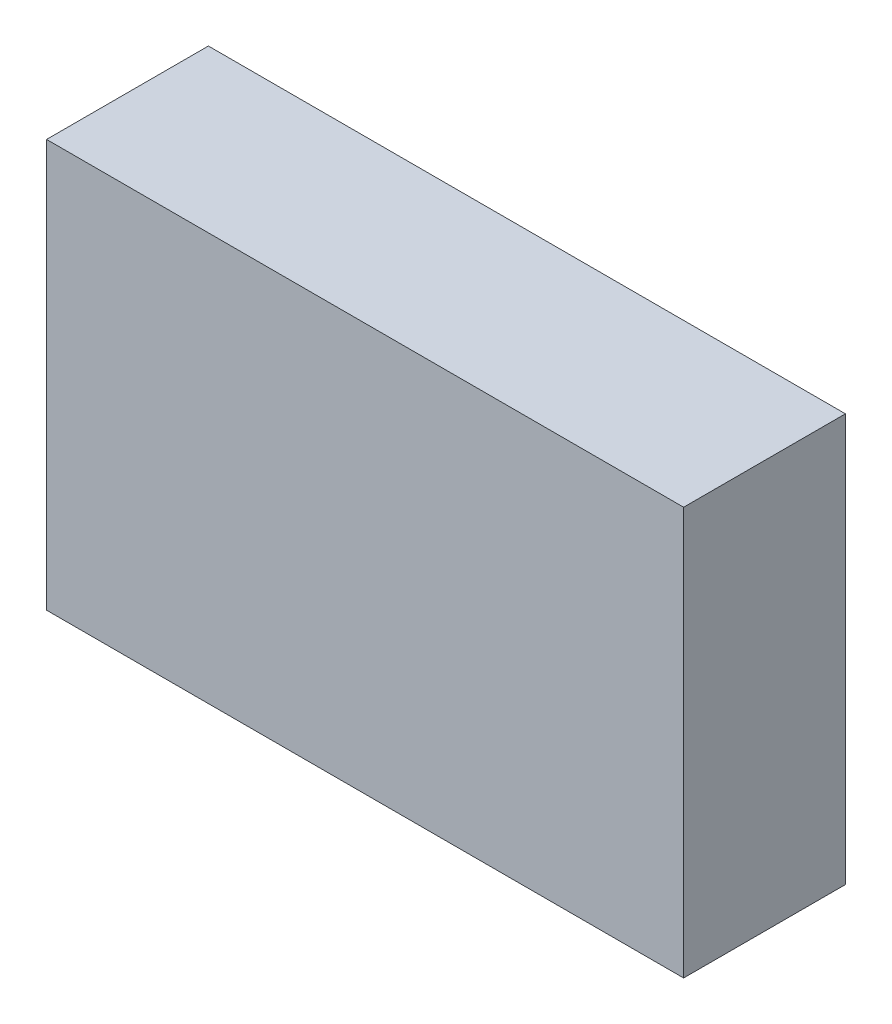
SolidWorks part; units mm, degrees
material "Aleación 1060"
ref_plane "Alzado" through (0, 0, 0) normal (0, 0, 1) x (1, 0, 0)
ref_plane "Planta" through (0, 0, 0) normal (0, 1, 0) x (1, 0, 0)
ref_plane "Vista lateral" through (0, 0, 0) normal (1, 0, 0) x (0, 0, -1)
sketch "Croquis1" plane through (0, 0, 0) normal (0, 0, 1) x (1, 0, 0)
  line L1 (25, -16) -> (-25, -16)
  line L2 (25, -16) -> (25, 16)
  line L3 (25, 16) -> (-25, 16)
  line L4 (-25, -16) -> (-25, 16)
  line L5 (25, -16) -> (-25, 16) construction
  line L6 (25, 16) -> (-25, -16) construction
  point P0 (0, 0)
  dimension "D1" = 50
  dimension "D2" = 32
extrude "Saliente-Extruir1" add sketch "Croquis1" along normal blind 12.7
